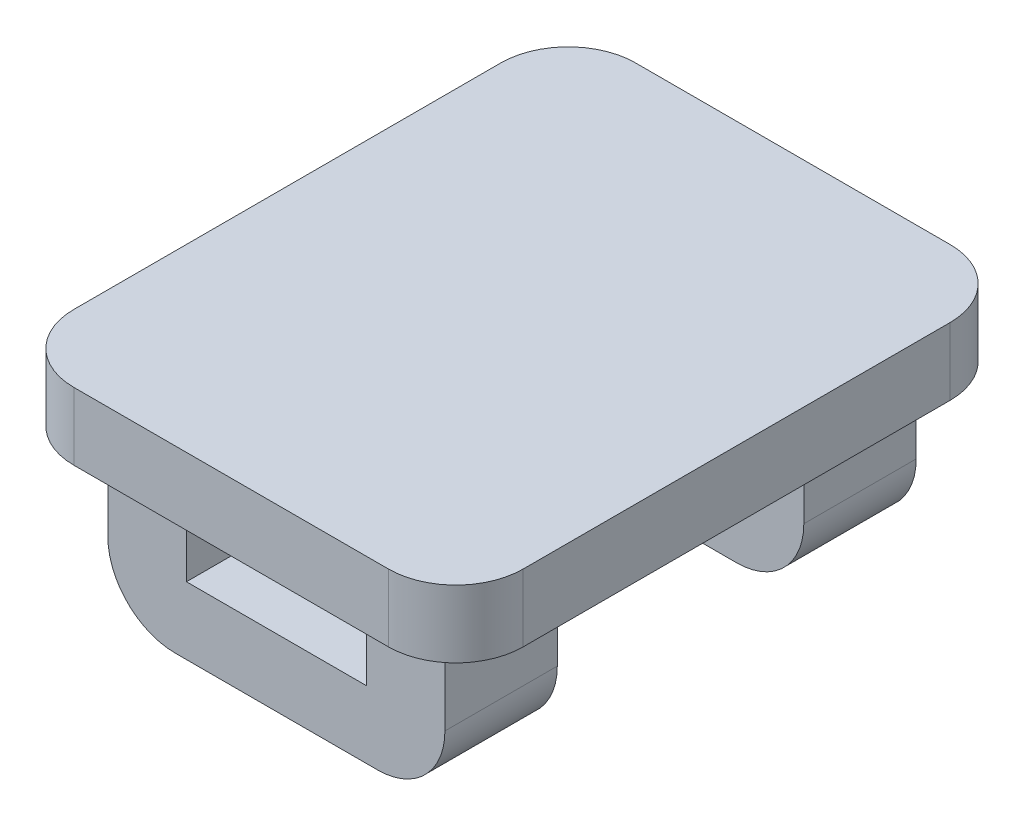
SolidWorks part; units mm, degrees
ref_plane "Plano frontal" through (0, 0, 0) normal (0, 0, 1) x (1, 0, 0)
ref_plane "Plano superior" through (0, 0, 0) normal (0, 1, 0) x (1, 0, 0)
ref_plane "Plano direito" through (0, 0, 0) normal (1, 0, 0) x (0, 0, -1)
sketch "Esboço1" plane through (0, 0, 0) normal (0, 1, 0) x (1, 0, 0)
  line L1 (-10, -12.5) -> (10, -12.5)
  line L2 (-10, -12.5) -> (-10, 12.5)
  line L3 (-10, 12.5) -> (10, 12.5)
  line L4 (10, -12.5) -> (10, 12.5)
  line L5 (-10, -12.5) -> (10, 12.5) construction
  line L6 (-10, 12.5) -> (10, -12.5) construction
  point P0 (0, 0)
  dimension "D1" = 25
  dimension "D2" = 20
extrude "Ressalto-extrusão1" add sketch "Esboço1" along normal blind 3
sketch "Esboço2" plane through (0, 0, 0) normal (0, -1, 0) x (-1, 0, 0)
  line L0 (-10, 0) -> (10, 0) construction
  line L5 (-7.5, 10.4849) -> (7.5, 10.4849)
  line L6 (-7.5, 10.4849) -> (-7.5, 5.4849)
  line L7 (-7.5, 5.4849) -> (7.5, 5.4849)
  line L8 (7.5, 10.4849) -> (7.5, 5.4849)
  line L9 (-7.5, 10.4849) -> (7.5, 5.4849) construction
  line L10 (-7.5, 5.4849) -> (7.5, 10.4849) construction
  line L11 (10, 12.5) -> (10, -12.5) construction
  line L12 (-7.5, -5.4849) -> (7.5, -10.4849) construction
  line L13 (-7.5, -10.4849) -> (7.5, -5.4849) construction
  line L14 (7.5, -10.4849) -> (7.5, -5.4849)
  line L15 (-7.5, -5.4849) -> (7.5, -5.4849)
  line L16 (-7.5, -10.4849) -> (-7.5, -5.4849)
  line L17 (-7.5, -10.4849) -> (7.5, -10.4849)
  point P0 (0, 7.9849)
  point P6 (0, 0)
  point P12 (0, 0)
  point P18 (0, -7.9849)
  dimension "D1" = 15
  dimension "D2" = 5
extrude "Ressalto-extrusão2" add sketch "Esboço2" along normal blind 7
fillet "Filete3" radius 3 4 edges at (10, 1.5, -12.5) (-10, 1.5, -12.5) (-10, 1.5, 12.5) (10, 1.5, 12.5)
sketch "Esboço4" plane through (0, 0, -10.4849) normal (0, 0, -1) x (-1, 0, 0)
  line L0 (7.5, 0) -> (-7.5, 0) construction
  line L1 (-4, -1) -> (4, -1)
  line L2 (-4, -1) -> (-4, -4)
  line L3 (-4, -4) -> (4, -4)
  line L4 (4, -1) -> (4, -4)
  line L5 (-4, -1) -> (4, -4) construction
  line L6 (-4, -4) -> (4, -1) construction
  point P0 (0, -2.5)
  point P5 (0, 0)
  dimension "D1" = 3
  dimension "D2" = 8
  dimension "D3" = 1
extrude "Corte-extrusão2" cut sketch "Esboço4" against normal through all
fillet "Filete4" radius 3 4 edges at (-7.5, -7, 7.9849) (7.5, -7, 7.9849) (-7.5, -7, -7.9849) (7.5, -7, -7.9849)
